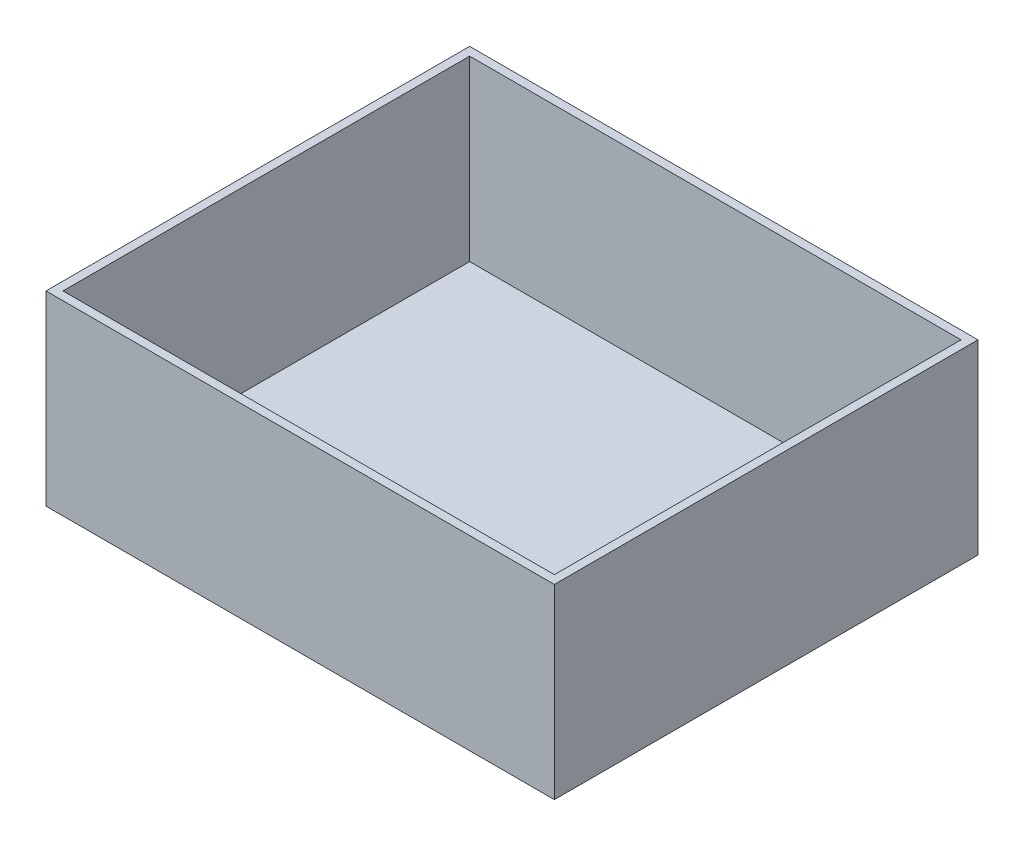
SolidWorks part; units mm, degrees
material "ENPH 253 Hardboard"
ref_plane "Front Plane" through (0, 0, 0) normal (0, 0, 1) x (1, 0, 0)
ref_plane "Top Plane" through (0, 0, 0) normal (0, 1, 0) x (1, 0, 0)
ref_plane "Right Plane" through (0, 0, 0) normal (1, 0, 0) x (0, 0, -1)
sketch "Sketch1" plane through (0, 0, 0) normal (0, 1, 0) x (1, 0, 0)
  line L1 (-90, 75) -> (90, 75)
  line L2 (-90, 75) -> (-90, -75)
  line L3 (-90, -75) -> (90, -75)
  line L4 (90, 75) -> (90, -75)
  line L5 (-90, 75) -> (90, -75) construction
  line L6 (-90, -75) -> (90, 75) construction
  point P0 (0, 0)
  dimension "D1" = 150
  dimension "D2" = 180
extrude "Boss-Extrude1" add sketch "Sketch1" along normal blind 66
shell "Shell1" thickness 3
